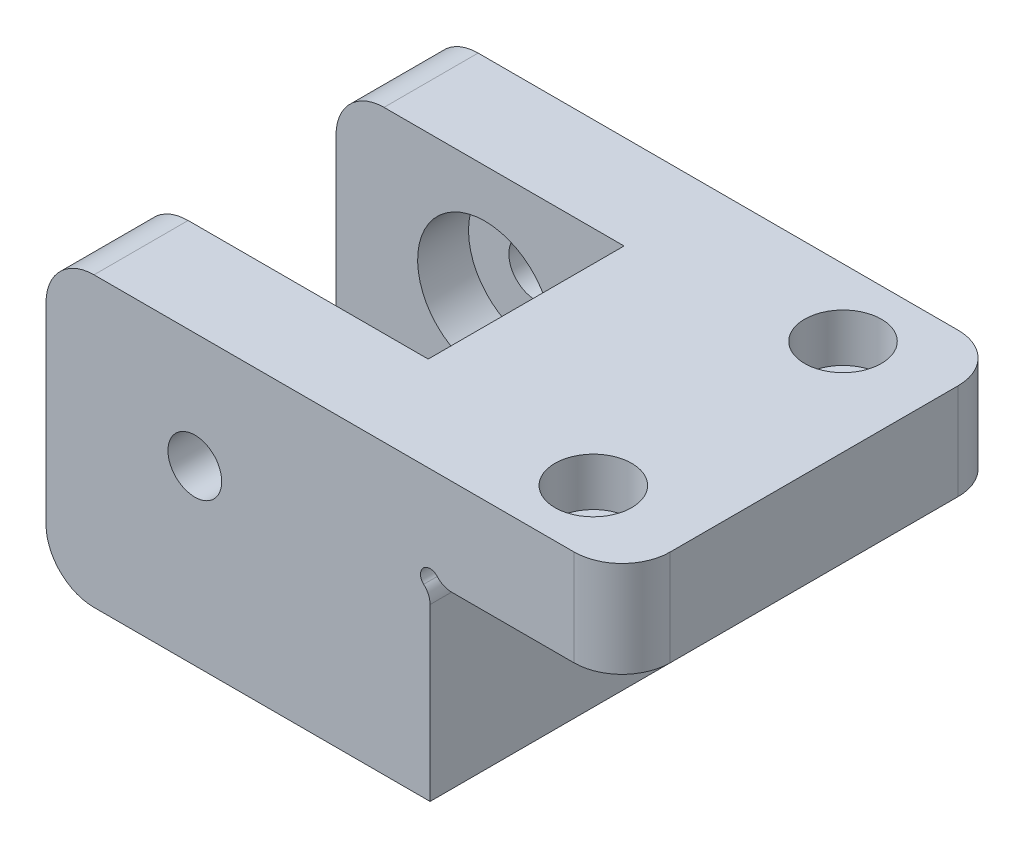
SolidWorks part; units mm, degrees
material "ABS"
ref_plane "Płaszczyzna przednia" through (0, 0, 0) normal (0, 0, 1) x (1, 0, 0)
ref_plane "Płaszczyzna górna" through (0, 0, 0) normal (0, 1, 0) x (1, 0, 0)
ref_plane "Płaszczyzna prawa" through (0, 0, 0) normal (1, 0, 0) x (0, 0, -1)
sketch "Szkic1" plane through (0, 0, 0) normal (0, 0, 1) x (1, 0, 0)
  line L0 (0, 0) -> (0, 17.7639)
  line L1 (2.2361, 20) -> (20, 20)
  line L2 (20, 20) -> (20, 30)
  line L3 (20, 30) -> (-10, 30)
  line L4 (-10, 30) -> (-10, 0)
  line L5 (-10, 0) -> (0, 0)
  arc A0 (0.7454, 20.6667) -> (-0.6667, 19.2546) centre (0, 20) ccw
  arc A1 (2.2361, 20) -> (0.7454, 20.6667) centre (2.2361, 22) cw
  arc A2 (0, 17.7639) -> (-0.6667, 19.2546) centre (-2, 17.7639) ccw
  dimension "D5" = 2
  dimension "D6" = 2
  dimension "D1" = 20
  dimension "D2" = 20
  dimension "D3" = 10
  dimension "D4" = 10
  dimension "D7" = 20
  dimension "D8" = 20
extrude "Dodanie-wyciągnięcie1" add sketch "Szkic1" along normal blind 40 contours L0 A2 A0 A1 L1 L2 L3 L4 L5
sketch "Szkic4" plane through (-10, 0, 0) normal (-1, 0, 0) x (0, 0, 1)
  line L0 (40, 30) -> (0, 30) construction
  line L1 (40, 0) -> (30.2, 0)
  line L2 (40, 0) -> (40, 30)
  line L3 (40, 30) -> (30.2, 30)
  line L4 (30.2, 0) -> (30.2, 30)
  line L5 (40, 0) -> (0, 0) construction
  line L6 (0, 30) -> (9.8, 30)
  line L7 (0, 30) -> (0, 0)
  line L8 (0, 0) -> (9.8, 0)
  line L9 (9.8, 30) -> (9.8, 0)
  dimension "D1" = 9.8
  dimension "D2" = 9.8
extrude "Dodanie-wyciągnięcie3" add sketch "Szkic4" along normal blind 30
sketch "Szkic6" plane through (0, 0, 40) normal (0, 0, 1) x (1, 0, 0)
  line L4 (-10, 0) -> (-10, 30)
  line L5 (-10, 30) -> (-40, 30)
  line L6 (-40, 30) -> (-40, 0)
  line L7 (-40, 0) -> (-10, 0)
  line L8 (-10, 0) -> (-10, 30)
  line L9 (-10, 30) -> (-40, 30)
  line L10 (-40, 30) -> (-40, 0)
  line L11 (-40, 0) -> (-10, 0)
  circle A0 centre (-24.5, 18) radius 7
  dimension "D2" = 14
  dimension "D4" = 14.5
  dimension "D3" = 18
  dimension "D1" = 0
extrude "Wytnij-wyciągnięcie1" cut sketch "Szkic6" against normal through all contours A0
sketch "Szkic7" plane through (-10, 0, 0) normal (-1, 0, 0) x (0, 0, 1)
  line L4 (0, 17.7639) -> (0, 0)
  line L5 (40, 17.7639) -> (0, 17.7639)
  line L6 (40, 0) -> (40, 17.7639)
  line L7 (0, 0) -> (40, 0)
  line L8 (0, 17.7639) -> (0, 0)
  line L9 (40, 17.7639) -> (0, 17.7639)
  line L10 (40, 0) -> (40, 17.7639)
  line L11 (0, 0) -> (40, 0)
  circle A0 centre (20, 10) radius 4
  point P7 (20, 0)
  dimension "D2" = 8
  dimension "D3" = 10
  dimension "D1" = 0
extrude "Wytnij-wyciągnięcie2" cut sketch "Szkic7" against normal blind 5 contours A0
sketch "Szkic8" plane through (-5, 0, 0) normal (-1, 0, 0) x (0, 0, 1)
  circle A0 centre (20, 10) radius 4 construction
  circle A1 centre (20, 10) radius 4
  circle A2 centre (20, 10) radius 2.1
  dimension "D1" = 4.2
extrude "Wytnij-wyciągnięcie3" cut sketch "Szkic8" against normal blind 5 contours A2
sketch "Szkic9" plane through (0, 30, 0) normal (0, 1, 0) x (1, 0, 0)
  line L4 (20, 0) -> (2.2361, 0)
  line L5 (20, -40) -> (20, 0)
  line L6 (2.2361, -40) -> (20, -40)
  line L7 (2.2361, 0) -> (2.2361, -40)
  line L8 (20, 0) -> (2.2361, 0)
  line L9 (20, -40) -> (20, 0)
  line L10 (2.2361, -40) -> (20, -40)
  line L11 (2.2361, 0) -> (2.2361, -40)
  circle A0 centre (10, -7) radius 4
  circle A1 centre (10, -33) radius 4
  dimension "D3" = 8
  dimension "D2" = 10
  dimension "D4" = 7
  dimension "D5" = 7
  dimension "D1" = 0
extrude "Wytnij-wyciągnięcie4" cut sketch "Szkic9" against normal blind 5 contours A1 | A0
sketch "Szkic10" plane through (0, 25, 0) normal (0, 1, 0) x (1, 0, 0)
  circle A0 centre (10, -7) radius 4 construction
  circle A1 centre (10, -33) radius 4 construction
  circle A2 centre (10, -7) radius 4
  circle A3 centre (10, -33) radius 4
  circle A4 centre (10, -7) radius 2.1
  circle A5 centre (10, -33) radius 2.1
  dimension "D1" = 4.2
extrude "Wytnij-wyciągnięcie5" cut sketch "Szkic10" against normal blind 5 contours A5 | A4
fillet "Zaokrąglenie1" radius 5 2 edges at (20, 25, 0) (20, 25, 40)
fillet "Zaokrąglenie2" radius 5 4 edges at (-40, 0, 4.9) (-40, 0, 35.1) (-40, 30, 35.1) (-40, 30, 4.9)
sketch "Szkic11" plane through (0, 0, 40) normal (0, 0, 1) x (1, 0, 0)
  circle A0 centre (-24.5, 18) radius 7 construction
  circle A1 centre (-24.5, 18) radius 7
extrude "Dodanie-wyciągnięcie5" add sketch "Szkic11" against normal blind 4.5
ref_plane "Płaszczyzna1" through (0, 0, 20) normal (0, 0, 1) x (1, 0, 0)
mirror "Lustro1" about plane through (0, 0, 20) normal (0, 0, 1) of "Dodanie-wyciągnięcie5"
sketch "Szkic12" plane through (0, 0, 40) normal (0, 0, 1) x (1, 0, 0)
  circle A0 centre (-24.5, 18) radius 7 construction
  circle A1 centre (-24.5, 18) radius 7 construction
  circle A2 centre (-24.5, 18) radius 2.8
  dimension "D1" = 5.6
extrude "Wytnij-wyciągnięcie6" cut sketch "Szkic12" against normal through all
